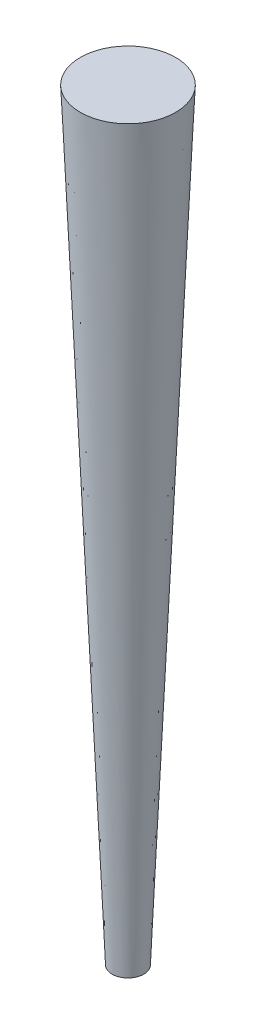
SolidWorks part; units mm, degrees
ref_plane "Front" through (0, 0, 0) normal (0, 0, 1) x (1, 0, 0)
ref_plane "Top" through (0, 0, 0) normal (0, 1, 0) x (1, 0, 0)
ref_plane "Right" through (0, 0, 0) normal (1, 0, 0) x (0, 0, -1)
other "Configuration Table"
sketch "Sketch1" plane through (0, 0, 0) normal (0, 0, 1) x (1, 0, 0)
  line L0 (0, 127) -> (0, -25.4) construction
  line L1 (0, 0) -> (0, 609.6)
  line L2 (0, 609.6) -> (38.1, 609.6)
  line L3 (0, 0) -> (12.7, 0)
  line L4 (38.1, 609.6) -> (12.7, 0)
  dimension "D1" = 609.6
  dimension "D2" = 38.1
  dimension "D3" = 12.7
revolve "Revolve1" add sketch "Sketch1" angle 360 about L0
